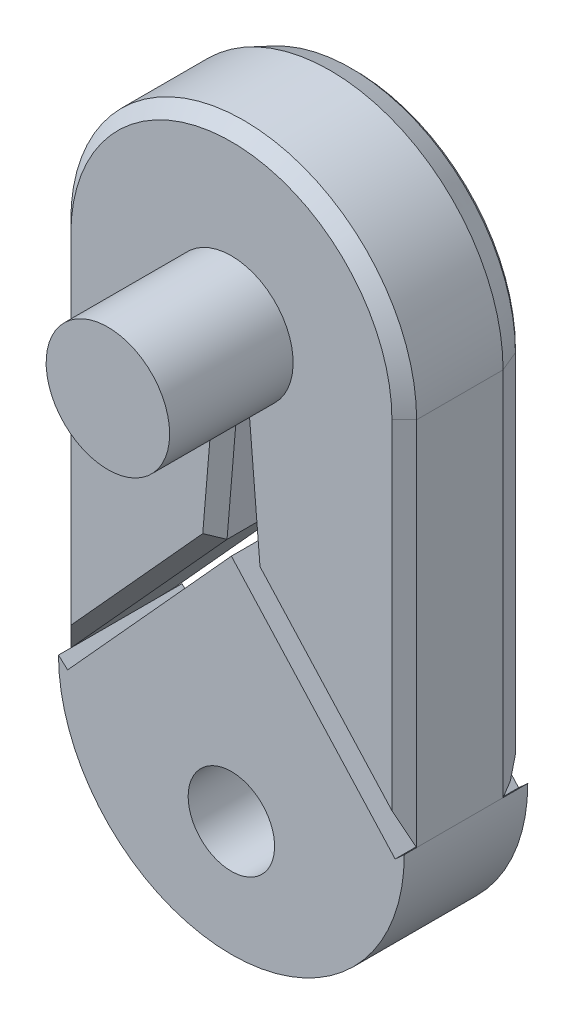
SolidWorks part; units mm, degrees
ref_plane "Front Plane" through (0, 0, 0) normal (0, 0, 1) x (1, 0, 0)
ref_plane "Top Plane" through (0, 0, 0) normal (0, 1, 0) x (1, 0, 0)
ref_plane "Right Plane" through (0, 0, 0) normal (1, 0, 0) x (0, 0, -1)
sketch "Sketch1" plane through (0, 0, 0) normal (0, 0, 1) x (1, 0, 0)
  line L0 (0, 0) -> (0, -30) construction
  line L1 (14, 0) -> (14, -30)
  line L2 (-14, 0) -> (-14, -30)
  arc A0 (14, 0) -> (-14, 0) centre (0, 0) ccw
  arc A1 (-14, -30) -> (14, -30) centre (0, -30) ccw
  point P3 (0, -15)
  dimension "D1" = 14
  dimension "D2" = 30
extrude "Boss-Extrude1" add sketch "Sketch1" along normal blind 10
sketch "Sketch2" plane through (0, 0, 10) normal (0, 0, 1) x (1, 0, 0)
  circle A0 centre (0, 0) radius 5
  dimension "D1" = 10
extrude "Boss-Extrude2" add sketch "Sketch2" along normal blind 10
sketch "Sketch3" plane through (0, 0, 0) normal (0, 0, -1) x (-1, 0, 0)
  circle A2 centre (0, -34.6645) radius 3.5
  dimension "D1" = 7
sketch "Sketch5" plane through (0, 0, 0) normal (0, 0, -1) x (-1, 0, 0)
  line L0 (-14, -30) -> (-1.3504, -16.0618)
  line L1 (1.3504, -16.0618) -> (14, -30)
  line L2 (-13.2595, -30.672) -> (0, -16.0618)
  line L3 (0, -16.0618) -> (13.2595, -30.672)
  line L4 (-13.2595, -30.672) -> (-14, -30)
  line L5 (14, -30) -> (13.2595, -30.672)
  line L6 (-1.3504, -16.0618) -> (0, 0)
  line L7 (0, 0) -> (1.3504, -16.0618)
  line L9 (0, -14.5738) -> (14, -30) construction
  line L10 (-14, -30) -> (0, -14.5738) construction
  dimension "D1" = 1
extrude "Cut-Extrude10" cut sketch "Sketch5" against normal blind 15
chamfer "Chamfer1" distance 1 angle 45 3 edges at (-14, -15, 10) (0, 14, 10) (14, -15, 10)
chamfer "Chamfer2" distance 1 angle 45 3 edges at (-14, -15, 0) (0, 14, 0) (14, -15, 0)
chamfer "Chamfer3" distance 1 angle 45 4 edges at (-7.1752, -22.48, 0) (7.1752, -22.48, 0) (0.6752, -8.0309, 0) (-0.6752, -8.0309, 0)
chamfer "Chamfer4" distance 1 angle 45 4 edges at (-7.1752, -22.48, 10) (-0.8847, -10.5221, 10) (7.1752, -22.48, 10) (0.8847, -10.5221, 10)
chamfer "Chamfer5" distance 1 3 edges at (14, -15, 1) (-14, -15, 1) (0, 14, 1)
extrude "Cut-Extrude11" cut sketch "Sketch3" against normal blind 10
